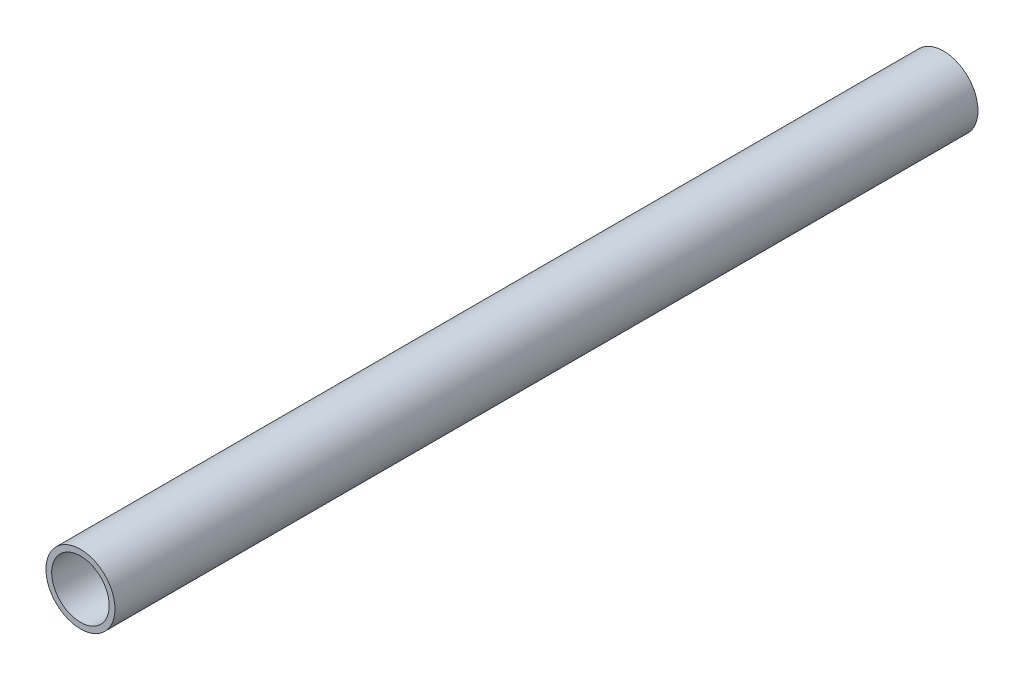
SolidWorks part; units mm, degrees
material "Thornel Mat VMA"
ref_plane "前视基准面" through (0, 0, 0) normal (0, 0, 1) x (1, 0, 0)
ref_plane "上视基准面" through (0, 0, 0) normal (0, 1, 0) x (1, 0, 0)
ref_plane "右视基准面" through (0, 0, 0) normal (1, 0, 0) x (0, 0, -1)
sketch "草图1" plane through (0, 0, 0) normal (0, 0, 1) x (1, 0, 0)
  circle A0 centre (0, 0) radius 6
  circle A1 centre (0, 0) radius 5
  dimension "D1" = 12
  dimension "D2" = 1
extrude "凸台-拉伸1" add sketch "草图1" along normal mid plane 150
